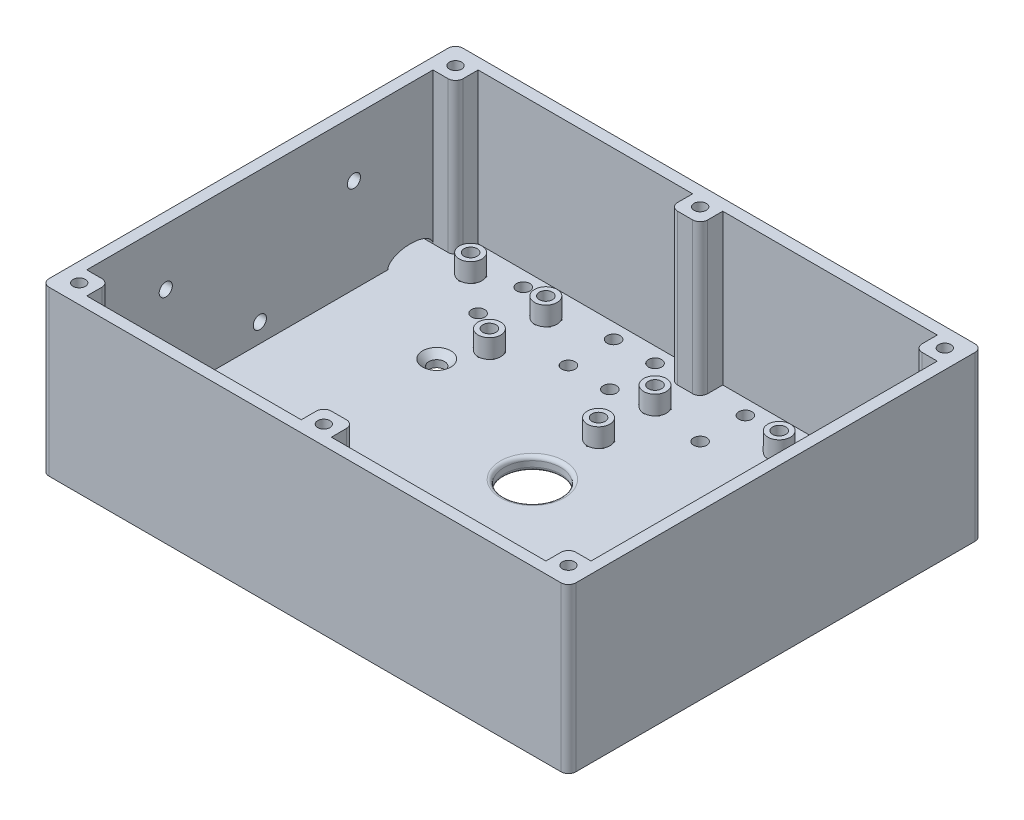
SolidWorks part; units mm, degrees
ref_plane "Front Plane" through (0, 0, 0) normal (0, 0, 1) x (1, 0, 0)
ref_plane "Top Plane" through (0, 0, 0) normal (0, 1, 0) x (1, 0, 0)
ref_plane "Right Plane" through (0, 0, 0) normal (1, 0, 0) x (0, 0, -1)
sketch "Sketch1" plane through (0, 0, 0) normal (0, 1, 0) x (1, 0, 0)
  line L1 (70, -55) -> (-70, -55)
  line L2 (70, -55) -> (70, 55)
  line L3 (70, 55) -> (-70, 55)
  line L4 (-70, -55) -> (-70, 55)
  line L5 (70, -55) -> (-70, 55) construction
  line L6 (70, 55) -> (-70, -55) construction
  point P0 (0, 0)
  dimension "D1" = 110
  dimension "D2" = 140
extrude "Bottom" add sketch "Sketch1" along normal blind 3.5
sketch "Sketch3" plane through (0, 3.5, 0) normal (0, 1, 0) x (1, 0, 0)
  line L0 (-70, 55) -> (70, 55)
  line L1 (70, 55) -> (70, -55)
  line L2 (70, -55) -> (-70, -55)
  line L3 (-70, -55) -> (-70, 55)
  line L4 (-61, 52) -> (-4, 52)
  line L5 (67, 46) -> (67, -46)
  line L6 (61, -52) -> (4, -52)
  line L7 (0, 55) -> (0, -55) construction
  line L8 (-67, 46) -> (-61, 46)
  line L9 (-61, 46) -> (-61, 52)
  line L10 (61, 52) -> (61, 46)
  line L11 (61, 46) -> (67, 46)
  line L12 (67, -46) -> (61, -46)
  line L13 (61, -46) -> (61, -52)
  line L14 (-67, -46) -> (-61, -46)
  line L15 (-61, -46) -> (-61, -52)
  line L16 (-67, -46) -> (-67, 46)
  line L17 (0, 0) -> (67, 0) construction
  line L18 (4, -52) -> (4, -46)
  line L19 (-4, 52) -> (-4, 46)
  line L20 (-4, 46) -> (4, 46)
  line L21 (4, 52) -> (4, 46)
  line L22 (0, 46) -> (0, 42.7097) construction
  line L23 (4, 52) -> (61, 52)
  line L24 (-4, -46) -> (4, -46)
  line L25 (-4, -52) -> (-4, -46)
  line L26 (-4, -52) -> (-61, -52)
  dimension "D1" = 3
  dimension "D2" = 3
  dimension "D3" = 3
  dimension "D4" = 3
  dimension "D5" = 6
  dimension "D6" = 8
extrude "Wall" add sketch "Sketch3" along normal blind 40
sketch "Sketch4" plane through (0, 43.5, 0) normal (0, 1, 0) x (1, 0, 0)
  line L0 (-70, 55) -> (-70, -55) construction
  line L1 (70, 55) -> (-70, 55) construction
  line L2 (70, -55) -> (70, 55) construction
  line L3 (-70, -55) -> (70, -55) construction
  line L4 (0, 55) -> (0, 30.3541) construction
  line L5 (70, 0) -> (33.8613, 0) construction
  circle A0 centre (-65, 50) radius 1.625
  circle A1 centre (65, 50) radius 1.625
  circle A2 centre (65, -50) radius 1.625
  circle A3 centre (-65, -50) radius 1.625
  circle A4 centre (0, 50) radius 1.625
  circle A5 centre (0, -50) radius 1.625
  dimension "D1" = 3.25
  dimension "D4" = 5
  dimension "D2" = 5
  dimension "D3" = 5
  dimension "D5" = 5
extrude "Top Plate Screw Holes" cut sketch "Sketch4" against normal blind 30 draft 1
fillet "Fillet14" radius 2 1 edges at (-4, 23.5, 46)
fillet "Fillet13" radius 2 1 edges at (4, 23.5, 46)
fillet "Fillet12" radius 2 1 edges at (-4, 23.5, -46)
fillet "Fillet11" radius 2 1 edges at (4, 23.5, -46)
fillet "Fillet1" radius 2 1 edges at (-61, 23.5, 46)
fillet "Fillet2" radius 2 1 edges at (61, 23.5, 46)
fillet "Fillet3" radius 2 1 edges at (61, 23.5, -46)
fillet "Fillet4" radius 2 1 edges at (-61, 23.5, -46)
fillet "Fillet5" radius 2 1 edges at (-70, 21.75, -55)
fillet "Fillet6" radius 2 1 edges at (70, 21.75, -55)
fillet "Fillet7" radius 2 1 edges at (70, 21.75, 55)
fillet "Fillet8" radius 2 1 edges at (-70, 21.75, 55)
sketch "M4 Mount" plane through (0, 3.5, 0) normal (0, -1, 0) x (1, 0, 0)
  line L0 (70, 53) -> (70, -53) construction
  line L1 (0, 0) -> (23.8675, 0) construction
  line L2 (0, 0) -> (0, -19.9393) construction
  circle A0 centre (40, -20) radius 2.1
  circle A1 centre (40, 20) radius 2.1
  circle A2 centre (-40, 20) radius 2.1
  circle A3 centre (-40, -20) radius 2.1
  dimension "D1" = 4.2
  dimension "D2" = 30
  dimension "D3" = 20
  dimension "D4" = 20
extrude "M4 Mount Cut" cut sketch "M4 Mount" along normal through all
sketch "M4 Screw Heads" plane through (0, 3.5, 0) normal (0, 1, 0) x (1, 0, 0)
  circle A0 centre (40, -20) radius 3.75
  circle A1 centre (40, 20) radius 3.75
  circle A2 centre (-40, 20) radius 3.75
  circle A3 centre (-40, -20) radius 3.75
  dimension "D1" = 7.5
extrude "Cut-Extrude3" cut sketch "M4 Screw Heads" against normal blind 10 draft 45
sketch "Sketch7" plane through (0, 0, 0) normal (0, -1, 0) x (1, 0, 0)
  line L0 (68, -55) -> (-68, -55) construction
  line L2 (0, -55) -> (0.5731, 13.4899) construction
  circle A0 centre (0.4184, -5) radius 7.5
  dimension "D1" = 15
  dimension "D2" = 50
extrude "USB Cabel Cut" cut sketch "Sketch7" against normal through all
fillet "Fillet9" radius 1 1 edges at (0.4184, 0, -12.5)
fillet "Fillet10" radius 1 1 edges at (0.4184, 3.5, 2.5)
sketch "Sketch8" plane through (0, 3.5, 0) normal (0, 1, 0) x (1, 0, 0)
  line L0 (0, 46) -> (0, 22.3123) construction
  line L1 (2, 46) -> (-2, 46) construction
  line L2 (-4, 52) -> (-61, 52) construction
  line L3 (-35, 52) -> (-35, 37.9688) construction
  circle A0 centre (-10, 48) radius 1.75
  circle A1 centre (-10, 36) radius 1.75
  circle A2 centre (14, 48) radius 1.75
  circle A3 centre (14, 36) radius 1.75
  circle A4 centre (-45, 48) radius 1.75
  circle A5 centre (-45, 36) radius 1.75
  circle A6 centre (-21, 48) radius 1.75
  circle A7 centre (-21, 36) radius 1.75
  dimension "D1" = 3.5
  dimension "D5" = 14
  dimension "D2" = 12
  dimension "D3" = 10
  dimension "D4" = 4
  dimension "D6" = 35
  dimension "D8" = 10
  dimension "D9" = 14
extrude "UV LAMP M3 CUT" cut sketch "Sketch8" against normal blind 10
sketch "M3 Connection" plane through (-67, 0, 0) normal (1, 0, 0) x (0, 0, -1)
  line L0 (46, 23.5) -> (13.1188, 23.5) construction
  line L1 (46, 43.5) -> (46, 3.5) construction
  line L2 (0, 3.5) -> (0, 17.9528) construction
  line L3 (46, 3.5) -> (-46, 3.5) construction
  circle A0 centre (25, 28.5) radius 1.75
  circle A1 centre (0, 8.5) radius 1.75
  circle A2 centre (-25, 28.5) radius 1.75
  dimension "D1" = 3.5
  dimension "D2" = 5
  dimension "D3" = 15
  dimension "D4" = 25
sketch "Cable Pass" plane through (-67, 0, 0) normal (1, 0, 0) x (0, 0, -1)
  line L0 (46, 3.5) -> (-46, 3.5) construction
  line L1 (46, 3.5) -> (34, 3.5)
  ellipse E0 centre (40, 3.5) end of major axis (34, 3.5) minor radius 3 (46, 3.5) -> (34, 3.5) ccw
  dimension "D1" = 12
  dimension "D2" = 3
extrude "M3 Connection CUT" cut sketch "M3 Connection" against normal blind 10
extrude "Cable Pass CUT" cut sketch "Cable Pass" against normal blind 10
sketch "Sketch9" plane through (0, 3.5, 0) normal (0, 1, 0) x (1, 0, 0)
  line L0 (67, -46) -> (67, 46) construction
  line L1 (-4, 52) -> (-61, 52) construction
  line L2 (-55, 44) -> (-35, 44) construction
  line L3 (-45, 44) -> (-45, 45.6151) construction
  line L4 (-45, 49.75) -> (-45, 46.25) construction
  line L6 (2, 46) -> (-2, 46) construction
  line L7 (0, 46) -> (0, 18.189) construction
  line L8 (2, 46) -> (-2, 46) construction
  circle A0 centre (47, 44) radius 3
  circle A1 centre (27, 44) radius 3
  circle A2 centre (47, 29) radius 3
  circle A3 centre (-35, 44) radius 3
  circle A4 centre (-35, 29) radius 3
  circle A5 centre (-55, 44) radius 3
  circle A6 centre (-45, 48) radius 1.75 construction
  circle A7 centre (0, 38) radius 3
  circle A8 centre (0, 23) radius 3
  dimension "D1" = 6
  dimension "D7" = 15
  dimension "D2" = 15
  dimension "D3" = 20
  dimension "D4" = 20
  dimension "D5" = 20
  dimension "D6" = 8
  dimension "D8" = 8
extrude "Curcuit Board Mount Posts EXT" add sketch "Sketch9" along normal blind 5
sketch "Sketch10" plane through (0, 8.5, 0) normal (0, 1, 0) x (1, 0, 0)
  circle A0 centre (-55, 44) radius 1.75
  circle A1 centre (-35, 44) radius 1.75
  circle A2 centre (-35, 29) radius 1.75
  circle A3 centre (27, 44) radius 1.75
  circle A4 centre (47, 44) radius 1.75
  circle A5 centre (47, 29) radius 1.75
  circle A6 centre (0, 38) radius 1.75
  circle A7 centre (0, 23) radius 1.75
  dimension "D1" = 3.5
extrude "M3 Screw Curcuit Mount CUT" cut sketch "Sketch10" against normal through all
sketch "Sketch11" plane through (0, 0, 0) normal (0, -1, 0) x (1, 0, 0)
  line L1 (-35, -47.1754) -> (-32.25, -45.5877)
  line L2 (-32.25, -45.5877) -> (-32.25, -42.4123)
  line L3 (-32.25, -42.4123) -> (-35, -40.8246)
  line L4 (-35, -40.8246) -> (-37.75, -42.4123)
  line L5 (-37.75, -42.4123) -> (-37.75, -45.5877)
  line L6 (-37.75, -45.5877) -> (-35, -47.1754)
  line L7 (-55, -47.1754) -> (-52.25, -45.5877)
  line L8 (-52.25, -45.5877) -> (-52.25, -42.4123)
  line L9 (-52.25, -42.4123) -> (-55, -40.8246)
  line L10 (-55, -40.8246) -> (-57.75, -42.4123)
  line L11 (-57.75, -42.4123) -> (-57.75, -45.5877)
  line L12 (-57.75, -45.5877) -> (-55, -47.1754)
  line L13 (-35, -32.1754) -> (-32.25, -30.5877)
  line L14 (-32.25, -30.5877) -> (-32.25, -27.4123)
  line L15 (-32.25, -27.4123) -> (-35, -25.8246)
  line L16 (-35, -25.8246) -> (-37.75, -27.4123)
  line L17 (-37.75, -27.4123) -> (-37.75, -30.5877)
  line L18 (-37.75, -30.5877) -> (-35, -32.1754)
  line L19 (27, -47.1754) -> (29.75, -45.5877)
  line L20 (29.75, -45.5877) -> (29.75, -42.4123)
  line L21 (29.75, -42.4123) -> (27, -40.8246)
  line L22 (27, -40.8246) -> (24.25, -42.4123)
  line L23 (24.25, -42.4123) -> (24.25, -45.5877)
  line L24 (24.25, -45.5877) -> (27, -47.1754)
  line L25 (47, -47.1754) -> (49.75, -45.5877)
  line L26 (49.75, -45.5877) -> (49.75, -42.4123)
  line L27 (49.75, -42.4123) -> (47, -40.8246)
  line L28 (47, -40.8246) -> (44.25, -42.4123)
  line L29 (44.25, -42.4123) -> (44.25, -45.5877)
  line L30 (44.25, -45.5877) -> (47, -47.1754)
  line L31 (47, -32.1754) -> (49.75, -30.5877)
  line L32 (49.75, -30.5877) -> (49.75, -27.4123)
  line L33 (49.75, -27.4123) -> (47, -25.8246)
  line L34 (47, -25.8246) -> (44.25, -27.4123)
  line L35 (44.25, -27.4123) -> (44.25, -30.5877)
  line L36 (44.25, -30.5877) -> (47, -32.1754)
  line L37 (0, -41.1754) -> (2.75, -39.5877)
  line L38 (2.75, -39.5877) -> (2.75, -36.4123)
  line L39 (2.75, -36.4123) -> (0, -34.8246)
  line L40 (0, -34.8246) -> (-2.75, -36.4123)
  line L41 (-2.75, -36.4123) -> (-2.75, -39.5877)
  line L42 (-2.75, -39.5877) -> (0, -41.1754)
  line L43 (0, -26.1754) -> (2.75, -24.5877)
  line L44 (2.75, -24.5877) -> (2.75, -21.4123)
  line L45 (2.75, -21.4123) -> (0, -19.8246)
  line L46 (0, -19.8246) -> (-2.75, -21.4123)
  line L47 (-2.75, -21.4123) -> (-2.75, -24.5877)
  line L48 (-2.75, -24.5877) -> (0, -26.1754)
  circle A0 centre (-35, -44) radius 2.75 construction
  circle A1 centre (-55, -44) radius 2.75 construction
  circle A2 centre (-35, -29) radius 2.75 construction
  circle A3 centre (27, -44) radius 2.75 construction
  circle A4 centre (47, -44) radius 2.75 construction
  circle A5 centre (47, -29) radius 2.75 construction
  circle A6 centre (47, -29) radius 1.75 construction
  circle A7 centre (0, -38) radius 2.75 construction
  circle A8 centre (0, -23) radius 2.75 construction
  dimension "D1" = 5.5
  dimension "D2" = 5.5
  dimension "D3" = 5.5
  dimension "D4" = 5.5
  dimension "D5" = 5.5
  dimension "D6" = 5.5
  dimension "D7" = 5.5
  dimension "D8" = 5.5
extrude "M3 Head Circuit Mount CUT" cut sketch "Sketch11" against normal blind 3.5
equation "\"BOXWALL\"=3"
equation "\"D1@Sketch3\"=\"BOXWALL\""
equation "\"D2@Sketch3\"=\"BOXWALL\""
equation "\"D3@Sketch3\"=\"BOXWALL\""
equation "\"D4@Sketch3\"=\"BOXWALL\""
equation "\"SCREW_M3\"=3.5"
equation "\"D1@Sketch8\"=\"SCREW_M3\""
equation "\"D1@M3 Connection\"=\"SCREW_M3\""
equation "\"D1@Sketch10\"=\"SCREW_M3\""
equation "\"SCREW_M3_HEAD\"=5.5"
equation "\"D1@Sketch11\"=\"SCREW_M3_HEAD\""
equation "\"D2@Sketch11\"=\"SCREW_M3_HEAD\""
equation "\"D3@Sketch11\"=\"SCREW_M3_HEAD\""
equation "\"D4@Sketch11\"=\"SCREW_M3_HEAD\""
equation "\"D5@Sketch11\"=\"SCREW_M3_HEAD\""
equation "\"D6@Sketch11\"=\"SCREW_M3_HEAD\""
equation "\"D7@Sketch11\"=\"SCREW_M3_HEAD\""
equation "\"D8@Sketch11\"=\"SCREW_M3_HEAD\""
